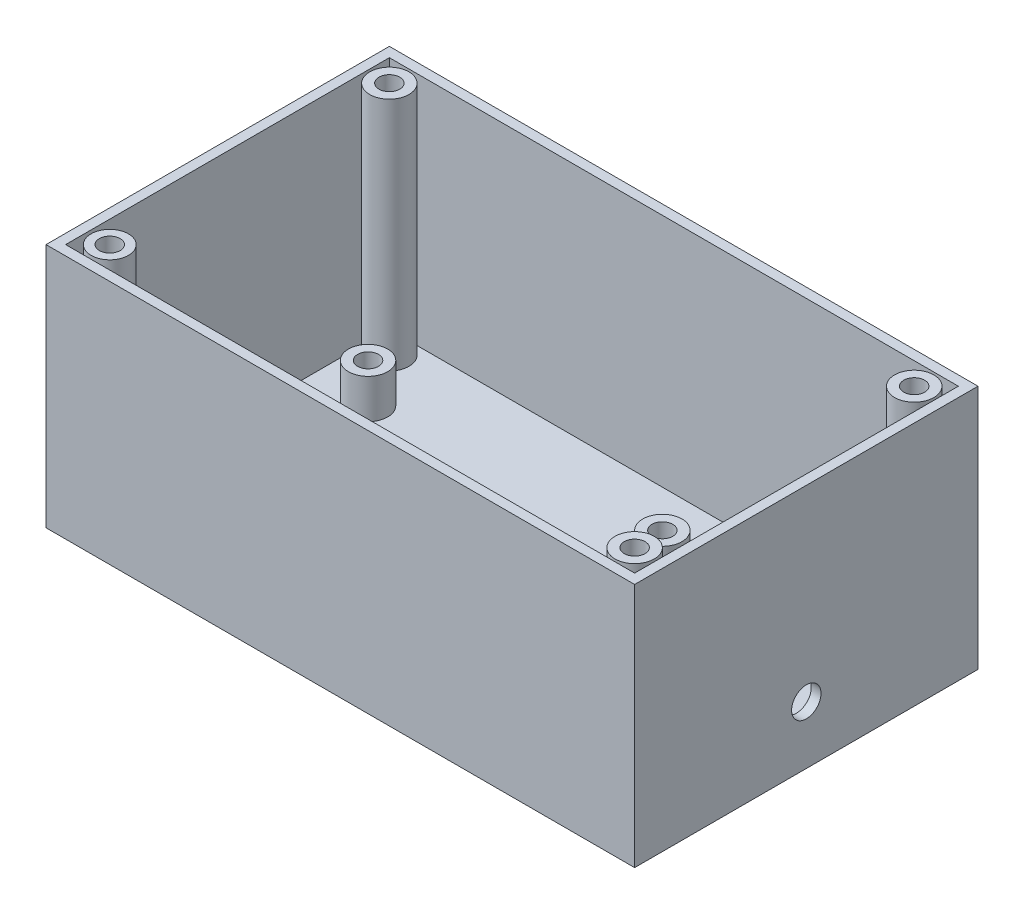
SolidWorks part; units mm, degrees
ref_plane "Front Plane" through (0, 0, 0) normal (0, 0, 1) x (1, 0, 0)
ref_plane "Top Plane" through (0, 0, 0) normal (0, 1, 0) x (1, 0, 0)
ref_plane "Right Plane" through (0, 0, 0) normal (1, 0, 0) x (0, 0, -1)
sketch "Sketch1" plane through (0, 0, 0) normal (0, 1, 0) x (1, 0, 0)
  line L1 (-60, 35) -> (60, 35)
  line L2 (-60, 35) -> (-60, -35)
  line L3 (-60, -35) -> (60, -35)
  line L4 (60, 35) -> (60, -35)
  line L5 (-60, 35) -> (60, -35) construction
  line L6 (-60, -35) -> (60, 35) construction
  line L7 (-58, 33) -> (58, 33)
  line L8 (-58, 33) -> (-58, -33)
  line L9 (-58, -33) -> (58, -33)
  line L10 (58, 33) -> (58, -33)
  line L11 (-58, 33) -> (58, -33) construction
  line L12 (-58, -33) -> (58, 33) construction
  point P0 (0, 0)
  point P6 (0, 0)
  dimension "D1" = 120
  dimension "D2" = 70
  dimension "D3" = 2
  dimension "D4" = 2
extrude "Boss-Extrude1" add sketch "Sketch1" along normal blind 50 contours L1 L4 L3 L2
sketch "Sketch3" plane through (0, 50, 0) normal (0, 1, 0) x (1, 0, 0)
  line L0 (-60, 35) -> (-60, -35) construction
  line L1 (-60, 35) -> (60, 35) construction
  line L2 (60, 35) -> (60, -35) construction
  line L3 (-60, -35) -> (60, -35) construction
  point P0 (0, 0)
  point P1 (-53.5, 0)
  point P2 (-53.5, -28.5)
  point P3 (0, -28.5)
  point P4 (53.5, -28.5)
  point P5 (53.5, 0)
  point P8 (-53.5, 28.5)
  point P9 (0, 28.5)
  point P10 (53.5, 28.5)
  point P11 (0, 0)
  point P12 (0, 0)
  point P13 (0, 0)
  dimension "D1" = 6.5
  dimension "D2" = 6.5
  dimension "D3" = 6.5
  dimension "D4" = 6.5
sketch "Sketch4" plane through (0, 50, 0) normal (0, 1, 0) x (1, 0, 0)
  line L0 (-60, 35) -> (60, 35) construction
  line L1 (-58, 33) -> (58, 33)
  line L2 (-58, 33) -> (-58, -33)
  line L3 (-58, -33) -> (58, -33)
  line L4 (58, 33) -> (58, -33)
  line L5 (-58, 33) -> (58, -33) construction
  line L6 (-58, -33) -> (58, 33) construction
  line L7 (60, 35) -> (60, -35) construction
  point P0 (0, 0)
  dimension "D1" = 2
  dimension "D2" = 2
extrude "Cut-Extrude1" cut sketch "Sketch4" against normal blind 48
sketch "Sketch5" plane through (0, 2, 0) normal (0, 1, 0) x (1, 0, 0)
  circle A0 centre (-53.5, 28.5) radius 2.125
  circle A2 centre (53.5, 28.5) radius 2.125
  circle A4 centre (53.5, -28.5) radius 2.125
  circle A6 centre (-53.5, -28.5) radius 2.125
  circle A7 centre (-53.5, 28.5) radius 4
  circle A8 centre (-53.5, -28.5) radius 3.8057
  circle A13 centre (53.5, -28.5) radius 4
  circle A15 centre (53.5, 28.5) radius 4
extrude "Boss-Extrude2" add sketch "Sketch5" along normal blind 48
sketch "Sketch7" plane through (0, 2, 0) normal (0, 1, 0) x (1, 0, 0)
  circle A0 centre (-46.7348, 17.3882) radius 2.125
  circle A1 centre (-46.7348, -17.8618) radius 2.125
  circle A2 centre (13.2652, -17.8618) radius 2.125
  circle A3 centre (13.2652, 17.3882) radius 2.125
  circle A4 centre (27.9892, 23.9843) radius 2.125
  circle A5 centre (41.9892, 23.9843) radius 2.125
  circle A6 centre (27.9892, -25.0157) radius 2.125
  circle A7 centre (41.9892, -25.0157) radius 2.125
  circle A8 centre (41.9892, 23.9843) radius 4
  circle A9 centre (27.9892, 23.9843) radius 4
  circle A10 centre (27.9892, -25.0157) radius 4
  circle A11 centre (41.9892, -25.0157) radius 4
  circle A12 centre (13.2652, -17.8618) radius 4
  circle A13 centre (13.2652, 17.3882) radius 4
  circle A14 centre (-46.7348, 17.3882) radius 4
  circle A15 centre (-46.7348, -17.8618) radius 4
  point P0 (-46.7348, 17.3882)
  point P1 (13.2652, 17.3882)
  point P2 (-46.7348, -17.8618)
  point P3 (13.2652, -17.8618)
  point P4 (41.9892, 23.9843)
  point P5 (27.9892, -25.0157)
  point P6 (27.9892, 23.9843)
  point P7 (41.9892, -25.0157)
  dimension "D1" = 60
  dimension "D2" = 14
  dimension "D3" = 35.25
  dimension "D4" = 49
extrude "Boss-Extrude3" add sketch "Sketch7" along normal blind 8
sketch "Sketch9" plane through (60, 0, 0) normal (1, 0, 0) x (0, 0, -1)
  circle A0 centre (0, 11.776) radius 3
sketch "Sketch10" plane through (-60, 0, 0) normal (-1, 0, 0) x (0, 0, 1)
  circle A0 centre (0, 11.776) radius 3
extrude "Cut-Extrude2" cut sketch "Sketch9" against normal blind 3 contours A0
extrude "Cut-Extrude3" cut sketch "Sketch10" against normal blind 3 contours A0
equation "\"D2@Sketch3\"=\"D1@Sketch3\""
equation "\"D3@Sketch3\"=\"D1@Sketch3\""
equation "\"D4@Sketch3\"=\"D1@Sketch3\""
equation "\"D4@Sketch1\"=\"D3@Sketch1\""
equation "\"D2@Sketch4\"=\"D1@Sketch4\""
